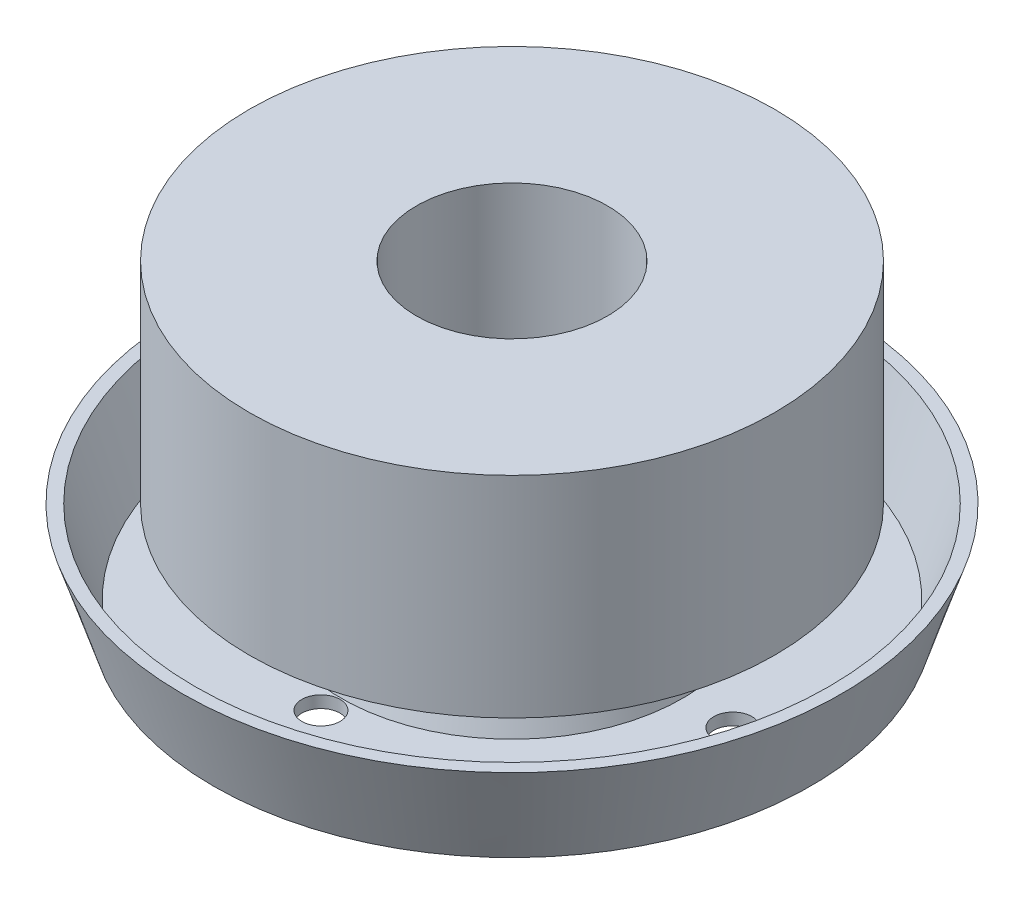
SolidWorks part; units mm, degrees
ref_plane "Front Plane" through (0, 0, 0) normal (0, 0, 1) x (1, 0, 0)
ref_plane "Top Plane" through (0, 0, 0) normal (0, 1, 0) x (1, 0, 0)
ref_plane "Right Plane" through (0, 0, 0) normal (1, 0, 0) x (0, 0, -1)
sketch "Sketch1" plane through (0, 0, 0) normal (0, 0, 1) x (1, 0, 0)
  line L0 (0, 0) -> (0, 12.8) construction
  line L1 (1.5, 4) -> (1.5, 0)
  line L2 (1.5, 0) -> (12.5, 0)
  line L3 (12.5, 0) -> (13.8, 4)
  line L4 (1.5, 4) -> (6, 4)
  line L5 (6, 4) -> (7.1375, 0.5)
  line L6 (7.1375, 0.5) -> (12.1368, 0.5)
  line L7 (12.1368, 0.5) -> (13.2743, 4)
  line L8 (13.2743, 4) -> (13.8, 4)
  line L9 (9.6371, 0.5) -> (9.6371, 0) construction
  line L10 (12.7055, 2.25) -> (13.181, 2.0955) construction
  dimension "D1" = 3
  dimension "D2" = 12.8
  dimension "D3" = 27.6
  dimension "D4" = 25
  dimension "D5" = 4
  dimension "D6" = 0.5
  dimension "D7" = 12
revolve "Revolve1" add sketch "Sketch1" angle 360 about L0
sketch "Sketch2" plane through (0, 4, 0) normal (0, 1, 0) x (1, 0, 0)
  circle A0 centre (0, 0) radius 11
  circle A1 centre (0, 0) radius 4
  dimension "D1" = 22
  dimension "D2" = 8
extrude "Boss-Extrude1" add sketch "Sketch2" along normal blind 8.8
hole_wizard "M2x0.4 Tapped Hole1" positions "Sketch4" profile "Sketch3" tap size "M2x0.4" standard "ANSI Metric"
sketch "Sketch4" plane through (0, 0, 0) normal (0, -1, 0) x (-1, 0, 0)
  line L0 (0, 8) -> (0, -8) construction
  line L1 (-9.25, 0) -> (9.25, 0) construction
  point P0 (0, 8)
  point P2 (0, -8)
  point P10 (-9.25, 0)
  point P12 (9.25, 0)
  dimension "D1" = 18.5
  dimension "D2" = 16
sketch "Sketch3" plane through (0, 0, -8) normal (1, 0, 0) x (0, 0, -1)
  line L0 (0, 0) -> (0, 0.5)
  line L1 (0, 0.5) -> (0.8, 0.5)
  line L2 (0.8, 0.5) -> (0.8, 0)
  line L5 (0.8, 0) -> (0, 0)
  line L11 (0, -6.35) -> (0, 107.95) construction
  dimension "Thread Major Dia." = 1.6
  dimension "Thru Tap Drill Depth" = 0.5
sketch "Sketch5" plane through (0, 0, 0) normal (0, -1, 0) x (1, 0, 0)
  line L0 (0, 0) -> (-8.8388, -8.8388) construction
  line L1 (0, -8) -> (0, 8) construction
  line L2 (9.25, 0) -> (-9.25, 0) construction
  line L3 (8.8388, -8.8388) -> (-8.8388, 8.8388) construction
  circle A0 centre (0, 0) radius 12.5 construction
  circle A1 centre (0, -8) radius 0.8 construction
  circle A2 centre (-9.25, 0) radius 0.8 construction
  dimension "D1" = 45
ref_plane "Plane1" through (0, 0, 0) normal (-0.7071, 0, -0.7071) x (-0.7071, 0, 0.7071)
sketch "Sketch6" plane through (0, 0, 0) normal (-0.7071, 0, -0.7071) x (-0.7071, 0, 0.7071)
  line L0 (13.8, 4) -> (-13.8, 4) construction
  line L1 (-1.25, 2.75) -> (1.25, 2.75) construction
  line L2 (-1.25, 3.475) -> (1.25, 3.475)
  line L3 (-1.25, 2.025) -> (1.25, 2.025)
  circle A0 centre (0, 2.75) radius 0.625 construction
  circle A1 centre (1.25, 2.75) radius 0.625 construction
  circle A2 centre (-1.25, 2.75) radius 0.625 construction
  arc A3 (-1.25, 3.475) -> (-1.25, 2.025) centre (-1.25, 2.75) ccw
  arc A4 (1.25, 2.025) -> (1.25, 3.475) centre (1.25, 2.75) ccw
  point P6 (-0.625, 2.75)
  point P8 (0.625, 2.75)
  point P11 (0, 2.75)
  dimension "D1" = 1.25
  dimension "D3" = 0.1
  dimension "D2" = 1.25
extrude "Boss-Extrude3" add sketch "Sketch6" along normal blind 5 and the other way up to next from offset 14
